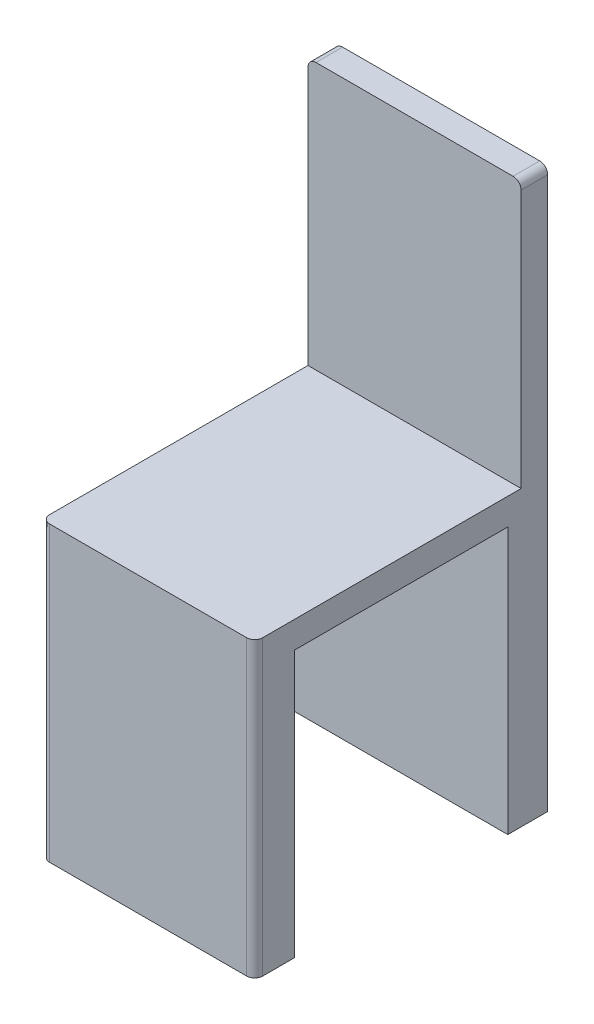
SolidWorks part; units mm, degrees
ref_plane "정면" through (0, 0, 0) normal (0, 0, 1) x (1, 0, 0)
ref_plane "윗면" through (0, 0, 0) normal (0, 1, 0) x (1, 0, 0)
ref_plane "우측면" through (0, 0, 0) normal (1, 0, 0) x (0, 0, -1)
sketch "스케치1" plane through (0, 0, 0) normal (1, 0, 0) x (0, 0, -1)
  line L0 (0, 0) -> (100, 0)
  line L1 (100, 0) -> (100, 100)
  line L2 (100, 100) -> (110, 100)
  line L3 (110, 100) -> (110, -10)
  line L4 (110, -10) -> (0, -10)
  line L5 (0, -10) -> (0, 0)
  line L8 (110, -10) -> (110, -110)
  line L9 (110, -110) -> (95, -110)
  line L10 (95, -10) -> (95, -110)
  line L12 (0, -10) -> (0, -110)
  line L13 (0, -110) -> (15, -110)
  line L14 (15, -10) -> (15, -110)
  dimension "D1" = 100
  dimension "D2" = 100
  dimension "D3" = 110
  dimension "D4" = 110
  dimension "D5" = 15
  dimension "D6" = 15
  dimension "D7" = 100
extrude "보스-돌출1" add sketch "스케치1" along normal blind 80 contours L5 L4 L3 L2 L1 L0 | L4 L10 L9 L8 | L14 L4 L12 L13
fillet "필렛1" radius 3 2 edges at (0, 100, -105) (80, 100, -105)
fillet "필렛2" radius 3 2 edges at (0, -55, 0) (80, -55, 0)
